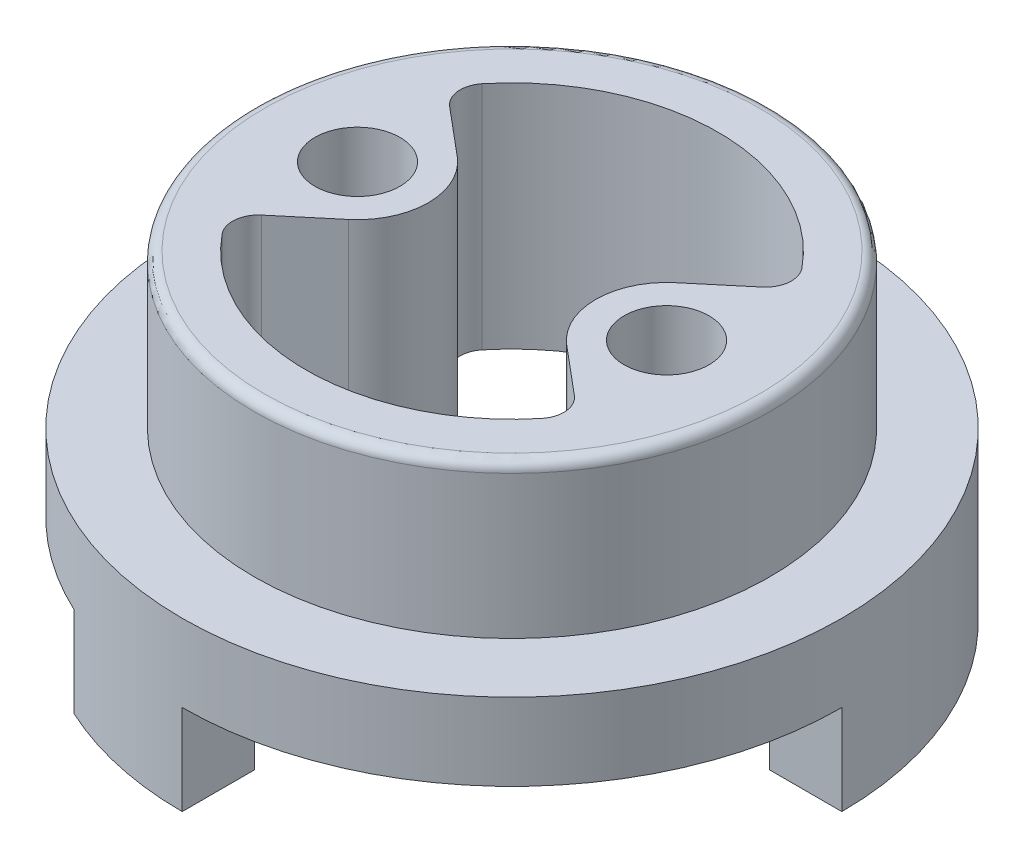
SolidWorks part; units mm, degrees
ref_plane "前视基准面" through (0, 0, 0) normal (0, 0, 1) x (1, 0, 0)
ref_plane "上视基准面" through (0, 0, 0) normal (0, 1, 0) x (1, 0, 0)
ref_plane "右视基准面" through (0, 0, 0) normal (1, 0, 0) x (0, 0, -1)
other "Configuration Table"
sketch "草图1" plane through (0, 0, 0) normal (0, 1, 0) x (1, 0, 0)
  circle A0 centre (0, 0) radius 12.8
  dimension "D1" = 25.6
extrude "凸台-拉伸1" add sketch "草图1" along normal blind 3
sketch "草图2" plane through (0, 3, 0) normal (0, 1, 0) x (1, 0, 0)
  circle A0 centre (0, 0) radius 10.01
  dimension "D1" = 20.02
extrude "凸台-拉伸2" add sketch "草图2" along normal blind 5.95
sketch "草图3" plane through (0, 8.95, 0) normal (0, 1, 0) x (1, 0, 0)
  circle A0 centre (0, 0) radius 8
  dimension "D1" = 16
extrude "切除-拉伸1" cut sketch "草图3" against normal through all
sketch "草图4" plane through (0, 0, 0) normal (0, 1, 0) x (1, 0, 0)
  line L0 (-6.7808, 4.2451) -> (-4.2323, 2.1066)
  line L1 (-4.2323, -2.1066) -> (-6.7808, -4.2451)
  line L2 (-16.8931, 0) -> (16.8931, 0) construction
  circle A0 centre (-6, 0) radius 1.65
  circle A1 centre (0, 0) radius 8 construction
  arc A2 (-6.7808, 4.2451) -> (-6.7808, -4.2451) centre (0, 0) ccw
  arc A3 (-4.2323, 2.1066) -> (-4.2323, -2.1066) centre (-6, 0) cw
  point P12 (0, 0)
  dimension "D1" = 3.3
  dimension "D2" = 2.75
  dimension "D3" = 80
  dimension "D4" = 6
extrude "凸台-拉伸3" add sketch "草图4" along normal up to surface (8.95 mm away) up to face at (0, 8.95, 8)
fillet "圆角1" radius 1 2 edges at (-6.7808, 4.475, 4.2451) (-6.7808, 4.475, -4.2451)
mirror "镜向1" about plane through (0, 0, 0) normal (1, 0, 0) of "圆角1", "凸台-拉伸3"
fillet "圆角2" radius 0.4 1 edges at (0, 8.95, 10.01)
sketch "草图5" plane through (0, 0, 0) normal (0, -1, 0) x (1, 0, 0)
  line L0 (0, 10) -> (0, 12.8) construction
  line L1 (-10, 0) -> (-12.8, 0) construction
  line L2 (10, 0) -> (12.8, 0) construction
  line L3 (0, -10) -> (0, -12.8) construction
  line L4 (-0.005, 12.8) -> (-0.005, 10)
  line L5 (0.005, 12.8) -> (0.005, 10)
  line L6 (12.8, -0.005) -> (10, -0.005)
  line L7 (12.8, 0.005) -> (10, 0.005)
  line L8 (-0.005, -12.8) -> (-0.005, -10)
  line L9 (0.005, -12.8) -> (0.005, -10)
  line L10 (-12.8, 0.005) -> (-10, 0.005)
  line L11 (-12.8, -0.005) -> (-10, -0.005)
  line L12 (-5.4095, 11.6007) -> (-4.2262, 9.0631)
  line L13 (-11.6007, 5.4095) -> (-9.0631, 4.2262)
  line L14 (0, 0) -> (-17.3342, 17.3342) construction
  circle A0 centre (0, 0) radius 12.8 construction
  circle A1 centre (0, 0) radius 12.8
  circle A2 centre (0, 0) radius 10
  point P31 (0, 0)
  circle M15 centre (0, 0) radius 12.8
  dimension "D1" = 20
  dimension "D2" = 0.01
  dimension "D4" = 40
  dimension "D5" = 45
  dimension "D3" = 4
extrude "凸台-拉伸4" add sketch "草图5" along normal blind 3.5 contours A2 L9 L6 M15 | A2 L13 L10 M15 | A2 L4 L12 M15
fillet "圆角3" radius 1 3 edges at (-2.1668, 0, 9.7624) (-9.7624, 0, 2.1668) (7.0711, 0, -7.0711)
